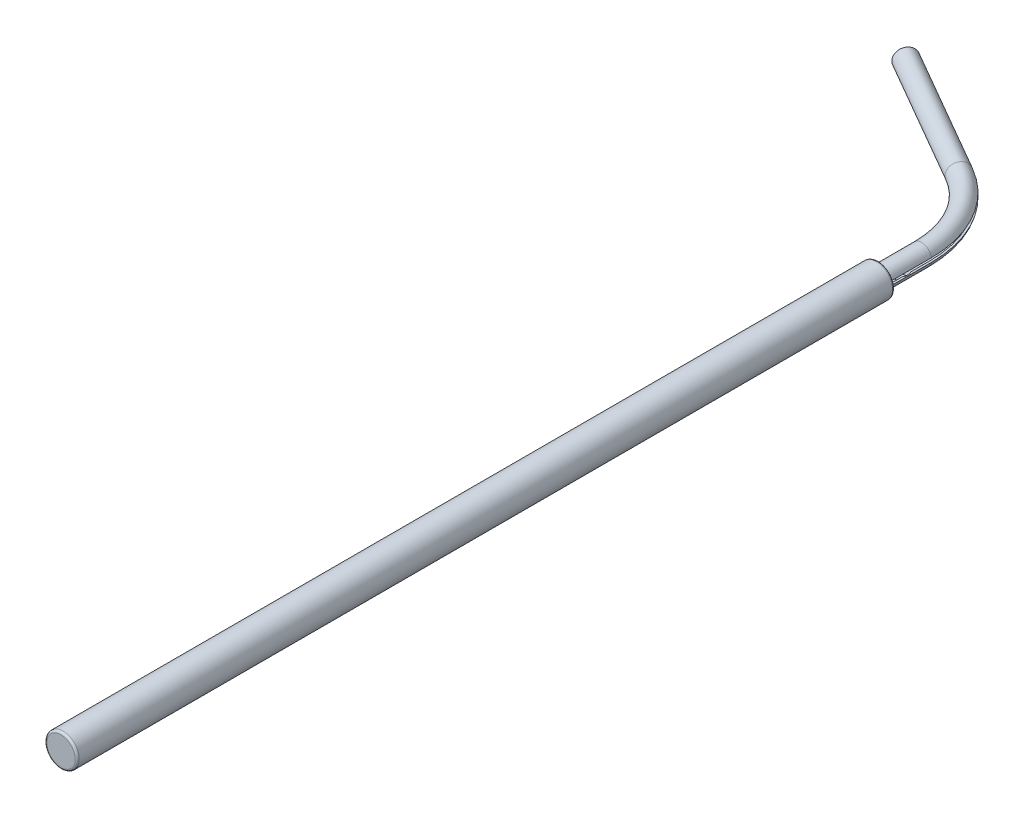
SolidWorks part; units mm, degrees
material "Pine"
ref_plane "Front Plane" through (0, 0, 0) normal (0, 0, 1) x (1, 0, 0)
ref_plane "Top Plane" through (0, 0, 0) normal (0, 1, 0) x (1, 0, 0)
ref_plane "Right Plane" through (0, 0, 0) normal (1, 0, 0) x (0, 0, -1)
sketch "Sketch1" plane through (0, 0, 0) normal (0, 0, 1) x (1, 0, 0)
  circle A0 centre (0, 0) radius 3.9688
  dimension "D1" = 7.9375
extrude "Extrude1" add sketch "Sketch1" against normal blind 200
fillet "Fillet1" radius 0.508 2 edges at (3.9688, 0, 0) (3.9688, 0, -200)
sketch "Sketch2" plane through (0, 0, 0) normal (0, 1, 0) x (1, 0, 0)
  line L0 (0, 200) -> (0, 210.5662)
  line L1 (3.4608, 200) -> (-3.4608, 200) construction
  line L2 (-12.5, 232.2169) -> (-43.3013, 250)
  arc A0 (-12.5, 232.2169) -> (0, 210.5662) centre (-25, 210.5662) cw
  point P7 (0, 225)
  point P8 (0, 225)
  dimension "D4" = 60
  dimension "D1" = 25
  dimension "D2" = 25
  dimension "D3" = 50
sketch "Sketch3" plane through (0, 0, -200) normal (0, 0, -1) x (-1, 0, 0)
  line L1 (-2.4495, 0.5) -> (-1.9365, 0.5)
  line L2 (-2.4495, 0.5) -> (-1.9365, 0.5) construction
  line L3 (-2.4495, 0.5) -> (-2.4495, -0.5) construction
  line L4 (-2.4495, -0.5) -> (-1.9365, -0.5) construction
  line L6 (-1.9365, -0.5) -> (-2.4495, -0.5)
  arc A0 (-1.9365, -0.5) -> (-1.9365, 0.5) centre (0, 0) ccw
  arc A1 (-2.4495, -0.5) -> (-2.4495, 0.5) centre (0, 0) ccw
  point P6 (-2.4495, 0)
  dimension "D1" = 5
  dimension "D3" = 4
  dimension "D2" = 1
sweep "Sweep1" add profiles "Sketch3" path "Sketch2"
ref_plane "Plane1" through (0, 0, -205) normal (0, 0, -1) x (-1, 0, 0)
sketch "Sketch4" plane through (0, 0, -205) normal (0, 0, -1) x (-1, 0, 0)
  line L0 (0, 0) -> (0, 3.9688) construction
  line L1 (0, 2.25) -> (0, -2.25)
  circle A0 centre (0, 0) radius 3.9688 construction
  arc A1 (0, -2.25) -> (0, 2.25) centre (0, 0) ccw
  dimension "D1" = 2.25
revolve "Cut-Revolve3" cut sketch "Sketch4" angle 360 about L0
equation "\"D1@Sketch3\" = \"D3@Sketch3\"+1"
equation "\"D1@Sketch4\" = (  \"D3@Sketch3\"+\"D1@Sketch3\")/4"
